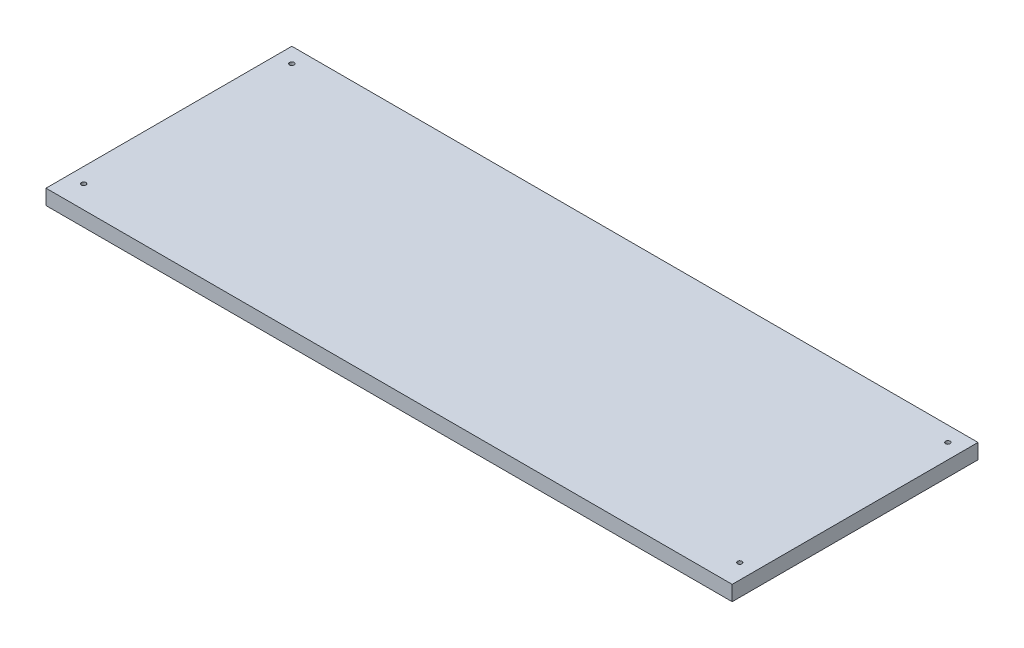
SolidWorks part; units mm, degrees
ref_plane "Front Plane" through (0, 0, 0) normal (0, 0, 1) x (1, 0, 0)
ref_plane "Top Plane" through (0, 0, 0) normal (0, 1, 0) x (1, 0, 0)
ref_plane "Right Plane" through (0, 0, 0) normal (1, 0, 0) x (0, 0, -1)
sketch "Sketch1" plane through (0, 0, 0) normal (0, 1, 0) x (1, 0, 0)
  line L1 (-227.5, -81.5) -> (227.5, -81.5)
  line L2 (-227.5, -81.5) -> (-227.5, 81.5)
  line L3 (-227.5, 81.5) -> (227.5, 81.5)
  line L4 (227.5, -81.5) -> (227.5, 81.5)
  line L5 (-227.5, -81.5) -> (227.5, 81.5) construction
  line L6 (-227.5, 81.5) -> (227.5, -81.5) construction
  point P0 (0, 0)
  dimension "D1" = 455
  dimension "D2" = 163
extrude "Boss-Extrude1" add sketch "Sketch1" along normal blind 10
hole_wizard "#32 (0.116) Diameter Hole1" positions "Sketch4" profile "Sketch3" hole size "#32" standard "ANSI Inch" end condition through all
sketch "Sketch4" plane through (0, 10, 0) normal (0, 1, 0) x (1, 0, 0)
  line L0 (227.5, -81.5) -> (227.5, 81.5) construction
  line L1 (-227.5, -81.5) -> (227.5, -81.5) construction
  line L2 (227.5, 81.5) -> (-227.5, 81.5) construction
  line L3 (-227.5, 81.5) -> (-227.5, -81.5) construction
  point P0 (217.5, -66.5)
  point P4 (217.5, 71.5)
  point P6 (-217.5, 71.5)
  point P8 (-217.5, -66.5)
  dimension "D1" = 10
  dimension "D2" = 15
  dimension "D3" = 10
  dimension "D4" = 10
  dimension "D5" = 10
  dimension "D6" = 10
  dimension "D7" = 10
  dimension "D8" = 15
sketch "Sketch3" plane through (217.5, 10, 66.5) normal (1, 0, 0) x (0, 0, 1)
  line L0 (0, 0) -> (0, 10)
  line L1 (0, 10) -> (1.5, 10)
  line L2 (1.5, 10) -> (1.5, 0)
  line L5 (1.5, 0) -> (0, 0)
  line L11 (0, -6.35) -> (0, 107.95) construction
  dimension "Thru Hole Dia." = 3
  dimension "Thru Hole Depth" = 10
